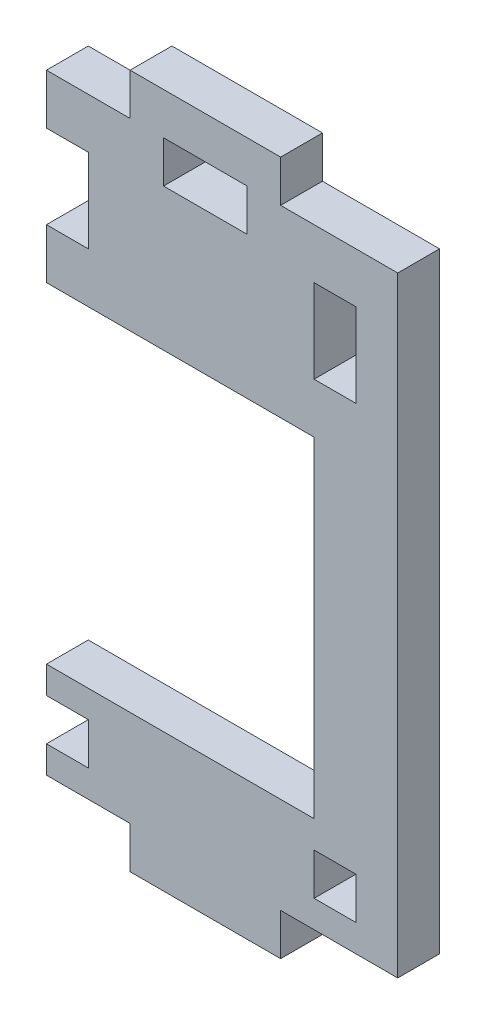
SolidWorks part; units mm, degrees
ref_plane "Plan de face" through (0, 0, 0) normal (0, 0, 1) x (1, 0, 0)
ref_plane "Plan de dessus" through (0, 0, 0) normal (0, 1, 0) x (1, 0, 0)
ref_plane "Plan de droite" through (0, 0, 0) normal (1, 0, 0) x (0, 0, -1)
sketch "Esquisse1" plane through (0, 0, 0) normal (0, 0, 1) x (1, 0, 0)
  line L0 (0, 73) -> (42, 73)
  line L1 (42, 73) -> (42, 0)
  line L2 (42, 0) -> (0, 0)
  line L3 (0, 0) -> (0, 11.5)
  line L5 (0, 11.5) -> (32, 11.5)
  line L6 (32, 11.5) -> (32, 51)
  line L7 (32, 51) -> (0, 51)
  line L8 (0, 51) -> (0, 73)
  dimension "D1" = 42
  dimension "D2" = 10
  dimension "D3" = 73
  dimension "D4" = 22
  dimension "D5" = 11.5
extrude "Boss.-Extru.1" add sketch "Esquisse1" along normal blind 5
sketch "Esquisse2" plane through (0, 0, 5) normal (0, 0, 1) x (1, 0, 0)
  line L0 (5, 0) -> (5, 73) construction
  line L1 (5, 67) -> (0, 67)
  line L2 (5, 67) -> (5, 57)
  line L3 (5, 57) -> (0, 57)
  line L4 (0, 67) -> (0, 57)
  line L5 (0, 73) -> (0, 51) construction
  line L6 (42, 73) -> (0, 73) construction
  line L7 (0, 11.5) -> (0, 0) construction
  line L8 (0, 8.25) -> (5, 8.25)
  line L9 (0, 8.25) -> (0, 3.25)
  line L10 (0, 3.25) -> (5, 3.25)
  line L11 (5, 8.25) -> (5, 3.25)
  line L12 (32, 11.5) -> (0, 11.5) construction
  line L14 (32, 67) -> (37, 67)
  line L15 (32, 67) -> (32, 57)
  line L16 (32, 57) -> (37, 57)
  line L17 (37, 67) -> (37, 57)
  line L19 (14, 68) -> (14, 73) construction
  line L20 (32, 8.25) -> (37, 8.25)
  line L21 (32, 8.25) -> (32, 3.25)
  line L22 (32, 3.25) -> (37, 3.25)
  line L23 (37, 8.25) -> (37, 3.25)
  line L24 (14, 73) -> (24, 73)
  line L25 (14, 73) -> (14, 68)
  line L26 (14, 68) -> (24, 68)
  line L27 (24, 73) -> (24, 68)
  dimension "D1" = 10
  dimension "D2" = 6
  dimension "D3" = 5
  dimension "D4" = 3.25
  dimension "D5" = 10
  dimension "D6" = 6
  dimension "D7" = 5
  dimension "D8" = 3.25
extrude "Enlèv. mat.-Extru.1" cut sketch "Esquisse2" against normal blind 5
sketch "Esquisse3" plane through (0, 0, 5) normal (0, 0, 1) x (1, 0, 0)
  line L0 (14, 73) -> (0, 73) construction
  line L1 (10, 73) -> (28, 73)
  line L2 (10, 73) -> (10, 78)
  line L3 (10, 78) -> (28, 78)
  line L4 (28, 73) -> (28, 78)
  line L5 (0, 73) -> (0, 67) construction
  line L6 (0, 0) -> (42, 0) construction
  line L7 (10, 0) -> (28, 0)
  line L8 (10, 0) -> (10, -5)
  line L9 (10, -5) -> (28, -5)
  line L10 (28, 0) -> (28, -5)
  line L11 (-36.9196, -5) -> (343.0804, -5) construction
  dimension "D1" = 10
  dimension "D2" = 18
  dimension "D3" = 5
  dimension "D4" = 10
  dimension "D5" = 18
extrude "Boss.-Extru.2" add sketch "Esquisse3" against normal blind 5
